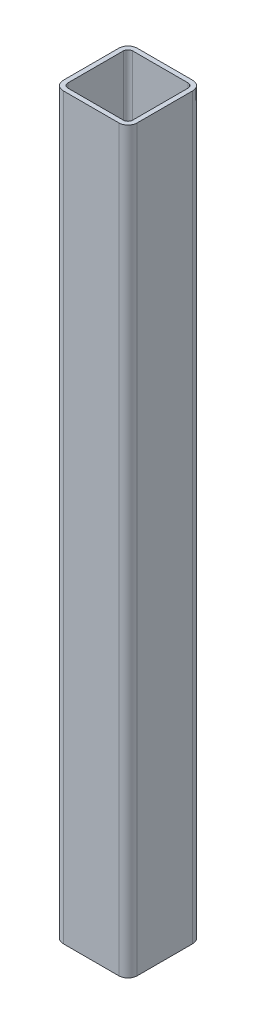
SolidWorks part; units mm, degrees
material "1.0037 (S235JR)"
ref_plane "Ön Düzlem" through (0, 0, 0) normal (0, 0, 1) x (1, 0, 0)
ref_plane "Üst Düzlem" through (0, 0, 0) normal (0, 1, 0) x (1, 0, 0)
ref_plane "Sağ Düzlem" through (0, 0, 0) normal (1, 0, 0) x (0, 0, -1)
sketch "Çizim1" plane through (0, 0, 0) normal (0, 0, 1) x (1, 0, 0)
  line L0 (0, 0) -> (0, 800)
  dimension "D1" = 800
other "Kare tüp 80 X 80 X 5(1)"
ref_plane "Düzlem1" through (0, 0, 0) normal (0, 1, 0) x (-1, 0, 0)
sketch "Sketch12" plane through (0, 0, 0) normal (0, 1, 0) x (-1, 0, 0)
  line L0 (-30, -35) -> (30, -35)
  line L1 (-35, -30) -> (-35, 30)
  line L2 (30, 35) -> (-30, 35)
  line L3 (35, 30) -> (35, -30)
  line L4 (-30, -40) -> (30, -40)
  line L5 (-40, -30) -> (-40, 30)
  line L6 (30, 40) -> (-30, 40)
  line L7 (40, 30) -> (40, -30)
  arc A0 (40, 30) -> (30, 40) centre (30, 30) ccw
  arc A1 (30, -40) -> (40, -30) centre (30, -30) ccw
  arc A2 (-40, -30) -> (-30, -40) centre (-30, -30) ccw
  arc A3 (-30, 40) -> (-40, 30) centre (-30, 30) ccw
  arc A4 (-30, 35) -> (-35, 30) centre (-30, 30) ccw
  arc A5 (35, 30) -> (30, 35) centre (30, 30) ccw
  arc A6 (30, -35) -> (35, -30) centre (30, -30) ccw
  arc A7 (-35, -30) -> (-30, -35) centre (-30, -30) ccw
  point P0 (-40, 0)
  point P1 (40, 0)
  point P2 (0, 40)
  point P3 (0, -40)
  point P4 (0, 0)
  point P5 (-40, -40)
  point P6 (40, -40)
  point P7 (40, 40)
  point P8 (-40, 40)
  point P33 (0, 0)
  dimension "D1" = 10
  dimension "Thickness" = 5
  dimension "V_leg" = 80
